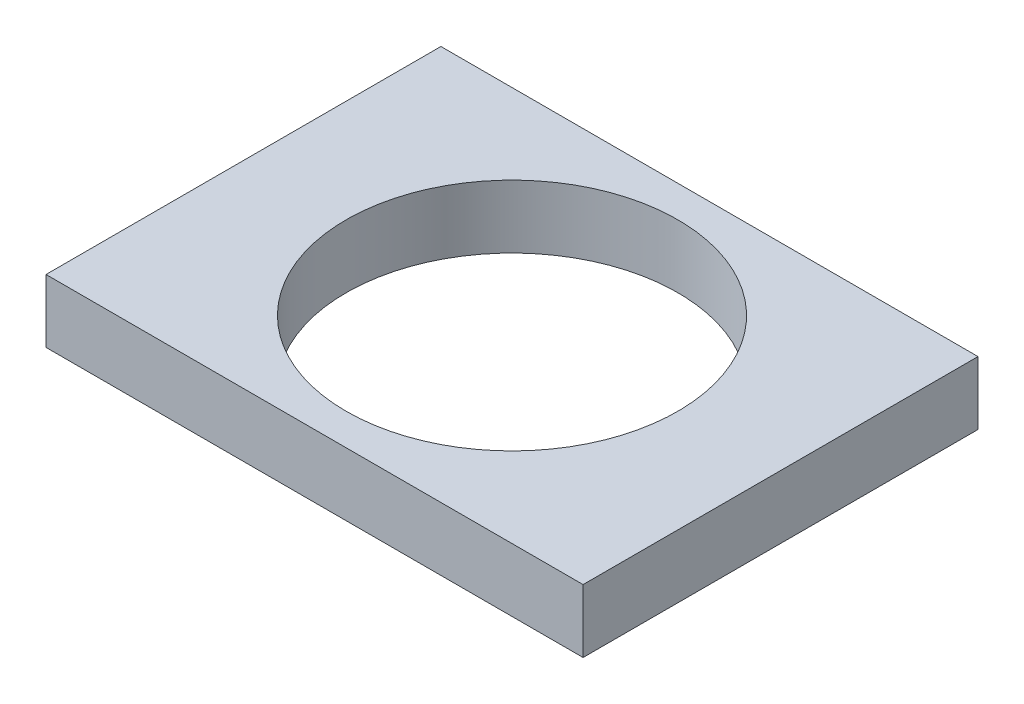
SolidWorks part; units mm, degrees
ref_plane "Front Plane" through (0, 0, 0) normal (0, 0, 1) x (1, 0, 0)
ref_plane "Top Plane" through (0, 0, 0) normal (0, 1, 0) x (1, 0, 0)
ref_plane "Right Plane" through (0, 0, 0) normal (1, 0, 0) x (0, 0, -1)
sketch "Sketch1" plane through (0, 0, 0) normal (0, 1, 0) x (1, 0, 0)
  line L1 (-85, -62.5) -> (85, -62.5)
  line L2 (-85, -62.5) -> (-85, 62.5)
  line L3 (-85, 62.5) -> (85, 62.5)
  line L4 (85, -62.5) -> (85, 62.5)
  line L5 (-85, -62.5) -> (85, 62.5) construction
  line L6 (-85, 62.5) -> (85, -62.5) construction
  circle A0 centre (0, 0) radius 52.5
  point P0 (0, 0)
  point P14 (0, 0)
  dimension "D3" = 105
  dimension "D1" = 125
  dimension "D2" = 170
extrude "Boss-Extrude1" add sketch "Sketch1" along normal blind 20 contours A0 | L2 L1 L4 L3
